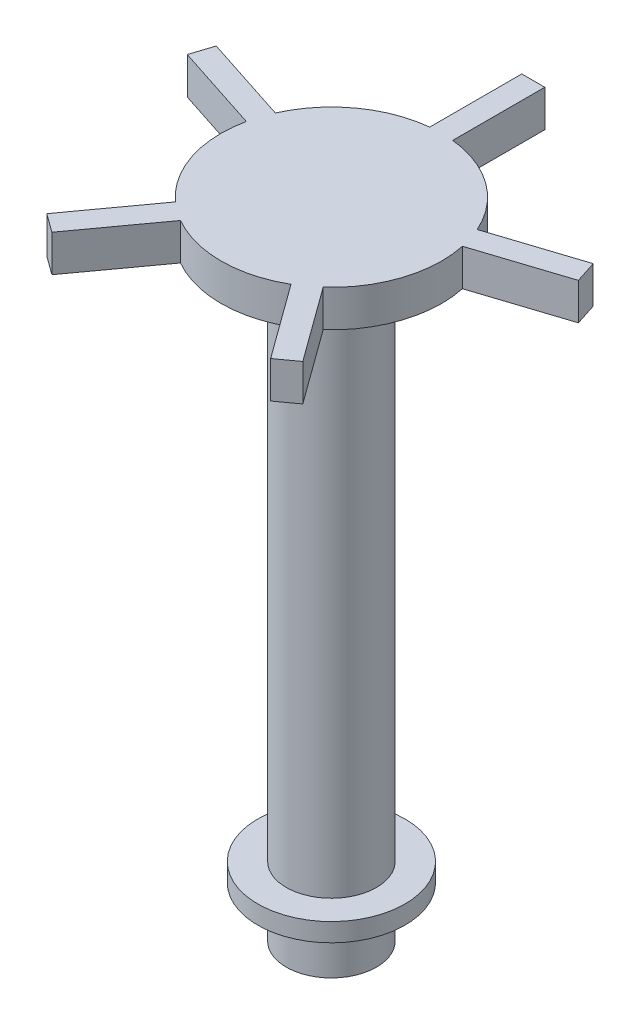
SolidWorks part; units mm, degrees
ref_plane "Front Plane" through (0, 0, 0) normal (0, 0, 1) x (1, 0, 0)
ref_plane "Top Plane" through (0, 0, 0) normal (0, 1, 0) x (1, 0, 0)
ref_plane "Right Plane" through (0, 0, 0) normal (1, 0, 0) x (0, 0, -1)
sketch "Sketch1" plane through (0, 0, 0) normal (0, 0, 1) x (1, 0, 0)
  line L0 (0, -35) -> (0, 35) construction
  line L1 (0, 35) -> (-12, 35)
  line L2 (-12, 35) -> (-12, 31)
  line L3 (-12, 31) -> (-4.9, 31)
  line L4 (-4.9, 31) -> (-4.9, -35)
  line L5 (-4.9, -35) -> (0, -35)
  line L6 (0, 35) -> (0, -35)
  line L7 (-4.9, -29.5) -> (-8, -29.5)
  line L8 (-8, -29.5) -> (-8, -27.5)
  line L9 (-8, -27.5) -> (-4.9, -27.5)
  point P4 (0, 0)
  dimension "D1" = 70
  dimension "D2" = 12
  dimension "D3" = 4.9
  dimension "D4" = 4
  dimension "D5" = 2
  dimension "D6" = 5.5
  dimension "D7" = 3.1
revolve "Revolve1" add sketch "Sketch1" angle 360 about L0
sketch "Sketch2" plane through (0, 35, 0) normal (0, 1, 0) x (1, 0, 0)
  line L0 (0, 0) -> (0, 12) construction
  line L1 (-1.25, 11.9347) -> (-1.25, 21.9347)
  line L2 (1.25, 11.9347) -> (1.25, 21.9347)
  line L3 (-1.25, 21.9347) -> (1.25, 21.9347)
  circle A1 centre (0, 0) radius 12
  arc A2 (1.25, 11.9347) -> (-1.25, 11.9347) centre (0, 0) ccw
  dimension "D2" = 10
  dimension "D3" = 1.25
  dimension "D1" = 0
extrude "Boss-Extrude1" add sketch "Sketch2" against normal up to surface (4 mm away) up to face at (0, 31, -4.9)
pattern_circular "CirPattern1" count 5 over 360 about axis through (0, 0, 0) along (0, 1, 0) of "Boss-Extrude1"
